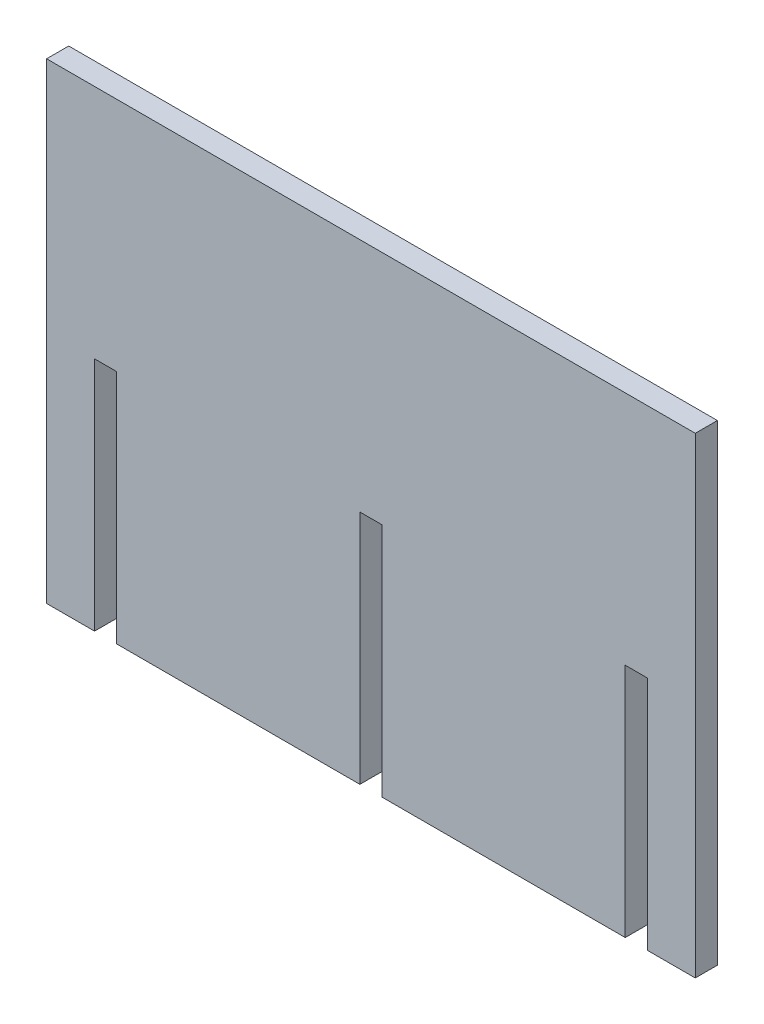
SolidWorks part; units mm, degrees
material "Corrugated Paper"
ref_plane "Front Plane" through (0, 0, 0) normal (0, 0, 1) x (1, 0, 0)
ref_plane "Top Plane" through (0, 0, 0) normal (0, 1, 0) x (1, 0, 0)
ref_plane "Right Plane" through (0, 0, 0) normal (1, 0, 0) x (0, 0, -1)
sketch "Sketch1" plane through (0, 0, 0) normal (0, 0, 1) x (1, 0, 0)
  line L1 (-69.85, -50.8) -> (69.85, -50.8)
  line L2 (-69.85, -50.8) -> (-69.85, 50.8)
  line L3 (-69.85, 50.8) -> (69.85, 50.8)
  line L4 (69.85, -50.8) -> (69.85, 50.8)
  line L5 (-69.85, -50.8) -> (69.85, 50.8) construction
  line L6 (-69.85, 50.8) -> (69.85, -50.8) construction
  point P0 (0, 0)
  dimension "D1" = 139.7
  dimension "D2" = 101.6
extrude "Boss-Extrude1" add sketch "Sketch1" along normal blind 4.7625
sketch "Sketch2" plane through (0, 0, 4.7625) normal (0, 0, 1) x (1, 0, 0)
  line L0 (-69.85, -50.8) -> (69.85, -50.8) construction
  line L1 (-59.5312, -101.6) -> (-54.7687, -101.6)
  line L2 (-59.5312, -101.6) -> (-59.5312, 0)
  line L3 (-59.5312, 0) -> (-54.7687, 0)
  line L4 (-54.7687, -101.6) -> (-54.7687, 0)
  line L5 (-59.5312, -101.6) -> (-54.7687, 0) construction
  line L6 (-59.5312, 0) -> (-54.7687, -101.6) construction
  line L7 (-69.85, 50.8) -> (-69.85, -50.8) construction
  point P0 (-57.15, -50.8)
  dimension "D1" = 4.7625
  dimension "D2" = 101.6
  dimension "D3" = 10.3187
extrude "Cut-Extrude1" cut sketch "Sketch2" against normal through all
pattern_linear "LPattern1" count 3 spacing 57.15 along (1, 0, 0) of "Cut-Extrude1"
